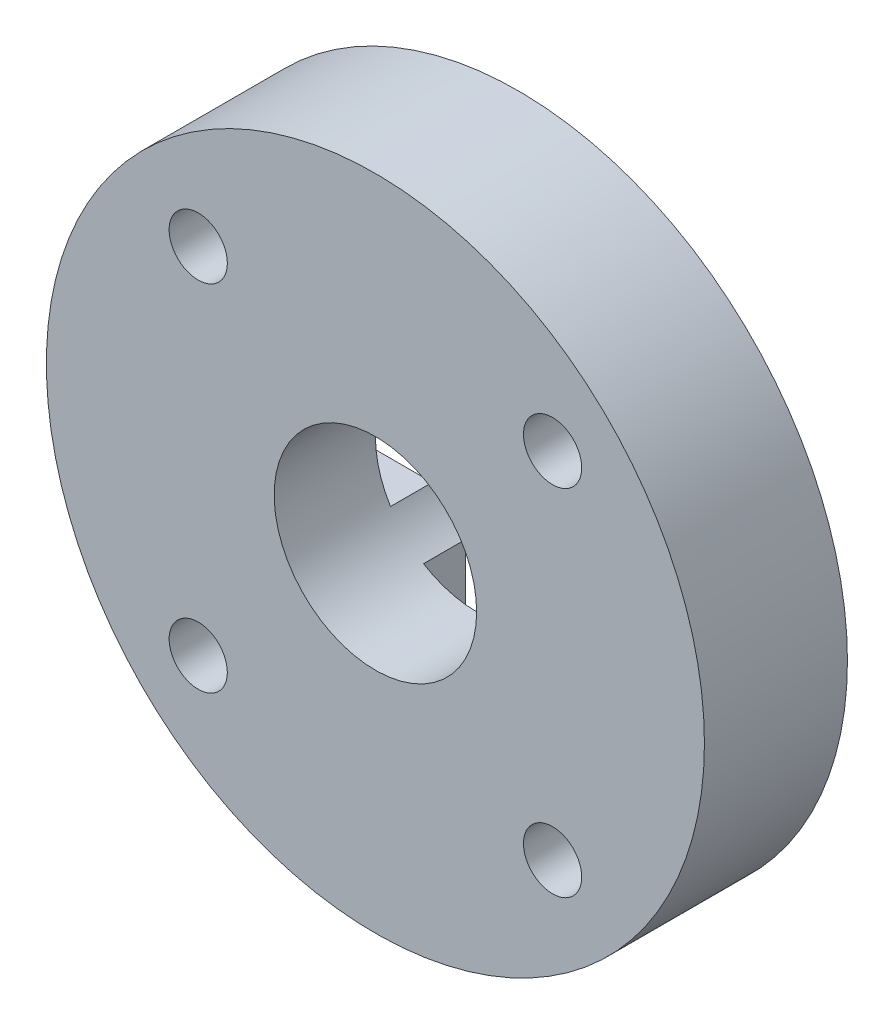
SolidWorks part; units mm, degrees
ref_plane "Front Plane" through (0, 0, 0) normal (0, 0, 1) x (1, 0, 0)
ref_plane "Top Plane" through (0, 0, 0) normal (0, 1, 0) x (1, 0, 0)
ref_plane "Right Plane" through (0, 0, 0) normal (1, 0, 0) x (0, 0, -1)
sketch "Trial_load_plate_profile" plane through (0, 0, 0) normal (0, 0, 1) x (1, 0, 0)
  circle A0 centre (0, 0) radius 13
  circle A1 centre (0, 0) radius 4
  dimension "D1" = 26
  dimension "D2" = 8
extrude "Trial_load_plate" add sketch "Trial_load_plate_profile" along normal blind 4
sketch "Captured_horn_key_boss_profile" plane through (0, 0, 0) normal (0, 0, 1) x (1, 0, 0)
  circle A0 centre (0, 0) radius 13
  dimension "D1" = 26
extrude "Captured_horn_key_boss" add sketch "Captured_horn_key_boss_profile" along normal blind 1.65 from offset 1.65
sketch "Stock_horn_pocket_Hub" plane through (0, 0, 0) normal (0, 0, 1) x (1, 0, 0)
  circle A0 centre (0, 0) radius 3.55
  dimension "D1" = 7.1
extrude "Key_pocket_Hub" cut sketch "Stock_horn_pocket_Hub" along normal blind 1.65 from offset 1.65
sketch "Stock_horn_pocket_Horizontal" plane through (0, 0, 0) normal (0, 0, 1) x (1, 0, 0)
  line L1 (-8.15, -2.1) -> (8.15, -2.1)
  line L2 (-8.15, -2.1) -> (-8.15, 2.1)
  line L3 (-8.15, 2.1) -> (8.15, 2.1)
  line L4 (8.15, -2.1) -> (8.15, 2.1)
  dimension "D1" = 16.3
  dimension "D2" = 4.2
  dimension "D3" = 8.15
  dimension "D4" = 2.1
extrude "Key_pocket_Horizontal" cut sketch "Stock_horn_pocket_Horizontal" along normal blind 1.65 from offset 1.65
sketch "Stock_horn_pocket_Vertical" plane through (0, 0, 0) normal (0, 0, 1) x (1, 0, 0)
  line L1 (-2.1, -8.15) -> (2.1, -8.15)
  line L2 (-2.1, -8.15) -> (-2.1, 8.15)
  line L3 (-2.1, 8.15) -> (2.1, 8.15)
  line L4 (2.1, -8.15) -> (2.1, 8.15)
  dimension "D1" = 4.2
  dimension "D2" = 16.3
  dimension "D3" = 2.1
  dimension "D4" = 8.15
extrude "Key_pocket_Vertical" cut sketch "Stock_horn_pocket_Vertical" along normal blind 1.65 from offset 1.65
sketch "Stock_horn_pocket_Rounded_tips" plane through (0, 0, 0) normal (0, 0, 1) x (1, 0, 0)
  circle A0 centre (8.15, 0) radius 2.1
  circle A1 centre (-8.15, 0) radius 2.1
  circle A2 centre (0, 8.15) radius 2.1
  circle A3 centre (0, -8.15) radius 2.1
  dimension "D1" = 4.2
  dimension "D2" = 4.2
  dimension "D3" = 4.2
  dimension "D4" = 4.2
  dimension "D5" = 8.15
  dimension "D6" = 8.15
  dimension "D7" = 8.15
  dimension "D8" = 8.15
extrude "Key_pocket_Rounded_tips" cut sketch "Stock_horn_pocket_Rounded_tips" along normal blind 1.65 from offset 1.65
sketch "Unmodified_horn_capture_M2_profile" plane through (0, 0, 0) normal (0, 0, 1) x (1, 0, 0)
  circle A0 centre (7, 7) radius 1.15
  circle A1 centre (-7, 7) radius 1.15
  circle A2 centre (-7, -7) radius 1.15
  circle A3 centre (7, -7) radius 1.15
  dimension "D1" = 2.3
  dimension "D2" = 2.3
  dimension "D3" = 2.3
  dimension "D4" = 2.3
  dimension "D5" = 7
  dimension "D6" = 7
  dimension "D7" = 7
  dimension "D8" = 7
extrude "Unmodified_horn_capture_M2" cut sketch "Unmodified_horn_capture_M2_profile" along normal through all from offset 50
sketch "Horn_center_hub_clearance" plane through (0, 0, 0) normal (0, 0, 1) x (1, 0, 0)
  circle A0 centre (0, 0) radius 4
  dimension "D1" = 8
extrude "Hub_clearance_in_key_boss_only" cut sketch "Horn_center_hub_clearance" along normal blind 1.65 from offset 1.65
